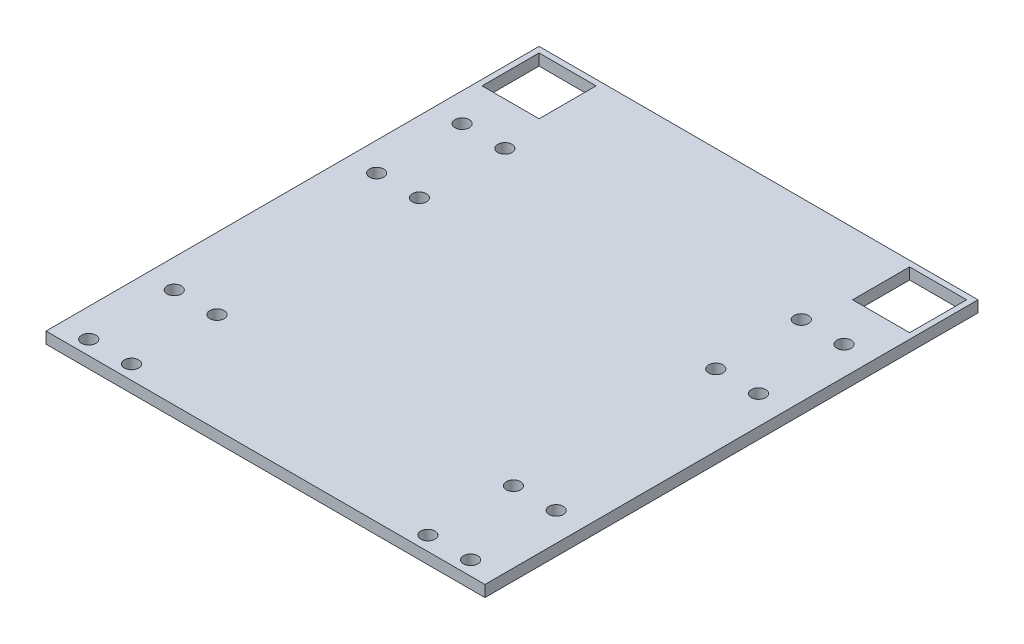
SolidWorks part; units mm, degrees
ref_plane "Front Plane" through (0, 0, 0) normal (0, 0, 1) x (1, 0, 0)
ref_plane "Top Plane" through (0, 0, 0) normal (0, 1, 0) x (1, 0, 0)
ref_plane "Right Plane" through (0, 0, 0) normal (1, 0, 0) x (0, 0, -1)
sketch "Sketch1" plane through (0, 0, 0) normal (0, 1, 0) x (1, 0, 0)
  line L1 (0, 0) -> (-154, 0)
  line L2 (0, 0) -> (0, -173)
  line L3 (0, -173) -> (-154, -173)
  line L4 (-154, 0) -> (-154, -173)
  dimension "D1" = 173
  dimension "D2" = 154
extrude "Boss-Extrude1" add sketch "Sketch1" along normal blind 4
sketch "Sketch2" plane through (0, 4, 0) normal (0, 1, 0) x (1, 0, 0)
  line L0 (-77, 0) -> (-77, -173) construction
  line L1 (-152, -2) -> (-132, -2)
  line L2 (-152, -2) -> (-152, -22)
  line L3 (-152, -22) -> (-132, -22)
  line L4 (-132, -2) -> (-132, -22)
  line L5 (0, 0) -> (-154, 0) construction
  line L6 (-154, -173) -> (0, -173) construction
  line L7 (-154, -86.5) -> (0, -86.5) construction
  line L8 (-154, 0) -> (-154, -173) construction
  line L9 (0, -173) -> (0, 0) construction
  line L18 (-22, -2) -> (-22, -22)
  line L19 (-2, -22) -> (-22, -22)
  line L20 (-2, -2) -> (-2, -22)
  line L21 (-2, -2) -> (-22, -2)
  circle A0 centre (-144, -37) radius 2.5
  circle A1 centre (-129, -37) radius 2.5
  circle A2 centre (-144, -67) radius 2.5
  circle A3 centre (-129, -67) radius 2.5
  circle A4 centre (-25, -67) radius 2.5
  circle A5 centre (-10, -67) radius 2.5
  circle A6 centre (-25, -37) radius 2.5
  circle A7 centre (-10, -37) radius 2.5
  circle A8 centre (-10, -168) radius 2.5
  circle A9 centre (-25, -168) radius 2.5
  circle A10 centre (-10, -138) radius 2.5
  circle A11 centre (-25, -138) radius 2.5
  circle A12 centre (-129, -138) radius 2.5
  circle A13 centre (-144, -138) radius 2.5
  circle A14 centre (-129, -168) radius 2.5
  circle A15 centre (-144, -168) radius 2.5
  dimension "D5" = 5
  dimension "D6" = 5
  dimension "D7" = 5
  dimension "D8" = 5
  dimension "D9" = 15
  dimension "D10" = 30
  dimension "D11" = 10
  dimension "D12" = 37
  dimension "D13" = 15
  dimension "D17" = 5
  dimension "D1" = 20
  dimension "D2" = 20
  dimension "D3" = 2
  dimension "D4" = 2
  dimension "D14" = 5
  dimension "D15" = 10
  dimension "D16" = 30
extrude "Cut-Extrude1" cut sketch "Sketch2" against normal blind 4
